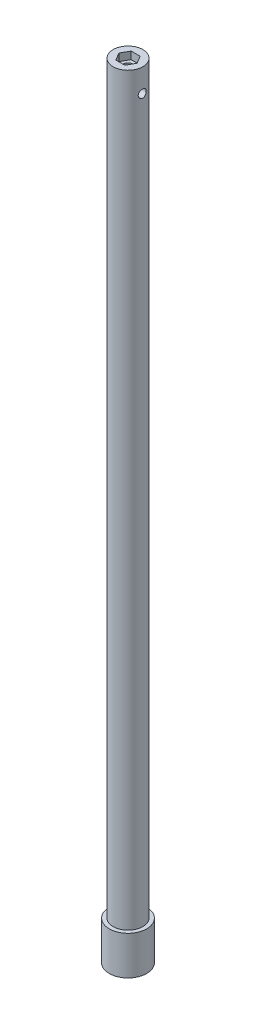
SolidWorks part; units mm, degrees
ref_plane "Front Plane" through (0, 0, 0) normal (0, 0, 1) x (1, 0, 0)
ref_plane "Top Plane" through (0, 0, 0) normal (0, 1, 0) x (1, 0, 0)
ref_plane "Right Plane" through (0, 0, 0) normal (1, 0, 0) x (0, 0, -1)
sketch "Sketch1" plane through (0, 0, 0) normal (0, 1, 0) x (1, 0, 0)
  circle A0 centre (0, 0) radius 5
  dimension "D1" = 10
extrude "Boss-Extrude1" add sketch "Sketch1" along normal mid plane 209.5
sketch "Sketch5" plane through (0, 104.75, 0) normal (0, 1, 0) x (1, 0, 0)
  circle A0 centre (0, 0) radius 3.975
  circle A1 centre (0, 0) radius 5
  circle A2 centre (0, 0) radius 5 construction
  dimension "D1" = 7.95
extrude "Cut-Extrude3" cut sketch "Sketch5" against normal blind 199.15
sketch "Sketch8" plane through (0, 104.75, 0) normal (0, 1, 0) x (1, 0, 0)
  line L1 (1.174, 2.0887) -> (-1.2219, 2.061)
  line L2 (-1.2219, 2.061) -> (-2.3958, -0.0277)
  line L3 (-2.3958, -0.0277) -> (-1.174, -2.0887)
  line L4 (-1.174, -2.0887) -> (1.2219, -2.061)
  line L5 (1.2219, -2.061) -> (2.3958, 0.0277)
  line L6 (2.3958, 0.0277) -> (1.174, 2.0887)
  circle A1 centre (0, 0) radius 2.075 construction
  dimension "D1" = 4.15
extrude "Cut-Extrude4" cut sketch "Sketch8" against normal blind 2
sketch "Sketch9" plane through (0, -94.4, 0) normal (0, 1, 0) x (1, 0, 0)
  circle A0 centre (0, 0) radius 11.05
  dimension "D1" = 22.1
sketch "Sketch10" plane through (0, -104.75, 0) normal (0, -1, 0) x (1, 0, 0)
  line L7 (0, 2.396) -> (-2.075, 1.198)
  line L8 (-2.075, 1.198) -> (-2.075, -1.198)
  line L9 (-2.075, -1.198) -> (0, -2.396)
  line L10 (0, -2.396) -> (2.075, -1.198)
  line L11 (2.075, -1.198) -> (2.075, 1.198)
  line L12 (2.075, 1.198) -> (0, 2.396)
  circle A0 centre (0, 0) radius 2.075 construction
  dimension "D1" = 4.15
extrude "Cut-Extrude5" cut sketch "Sketch10" against normal blind 2
sketch "Sketch11" plane through (0, -102.75, 0) normal (0, -1, 0) x (1, 0, 0)
  circle A0 centre (0, 0) radius 1.3
  dimension "D1" = 2.6
extrude "Cut-Extrude6" cut sketch "Sketch11" against normal blind 1
sketch "Sketch12" plane through (0, 102.75, 0) normal (0, 1, 0) x (1, 0, 0)
  circle A0 centre (0, 0) radius 1.3
  dimension "D1" = 2.6
extrude "Cut-Extrude7" cut sketch "Sketch12" against normal blind 1
sketch "Sketch13" plane through (0, 0, 0) normal (1, 0, 0) x (0, 0, -1)
  line L0 (-0.0277, 104.75) -> (-0.0277, 98.55) construction
  circle A0 centre (-0.0277, 98.55) radius 1.065
  dimension "D2" = 2.13
  dimension "D1" = 6.2
extrude "Cut-Extrude8" cut sketch "Sketch13" along normal through all both and the other way through all
sketch "Sketch14" plane through (0, 0, 0) normal (1, 0, 0) x (0, 0, -1)
  circle A0 centre (-0.0277, 98.55) radius 1.025
ref_plane "Plane1" through (0, 98.55, 0) normal (0, 1, 0) x (1, 0, 0)
sketch "Sketch16" plane through (0, 98.55, 0) normal (0, 1, 0) x (1, 0, 0)
  line L0 (-3.3511, 0) -> (11.6489, 0)
  line L1 (0, -3.0617) -> (0, 11.9383)
  dimension "D1" = 15
